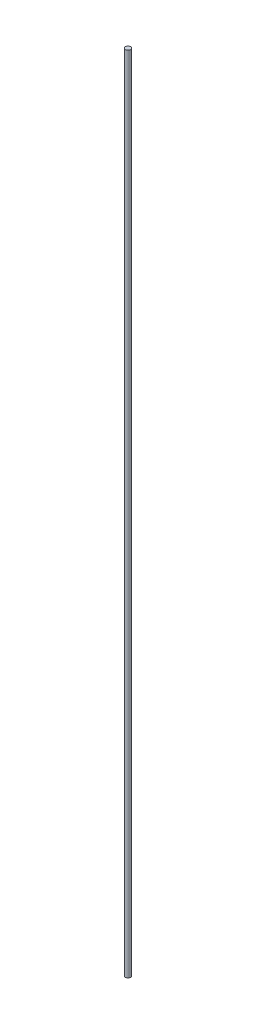
SolidWorks part; units mm, degrees
ref_plane "Front Plane" through (0, 0, 0) normal (0, 0, 1) x (1, 0, 0)
ref_plane "Top Plane" through (0, 0, 0) normal (0, 1, 0) x (1, 0, 0)
ref_plane "Right Plane" through (0, 0, 0) normal (1, 0, 0) x (0, 0, -1)
sketch "Sketch1" plane through (0, 0, 0) normal (0, 0, 1) x (1, 0, 0)
  line L0 (0, 0) -> (0, 1968.246)
  dimension "Length from Tank Model" = 1968.246
sweep "Sweep1" add path "Sketch1" circular profile diameter 12.7 parameters "D3"=12.7
equation "\"rebar diameter\"= .5"
equation "\"D3@Sweep1\"=\"rebar diameter\""
